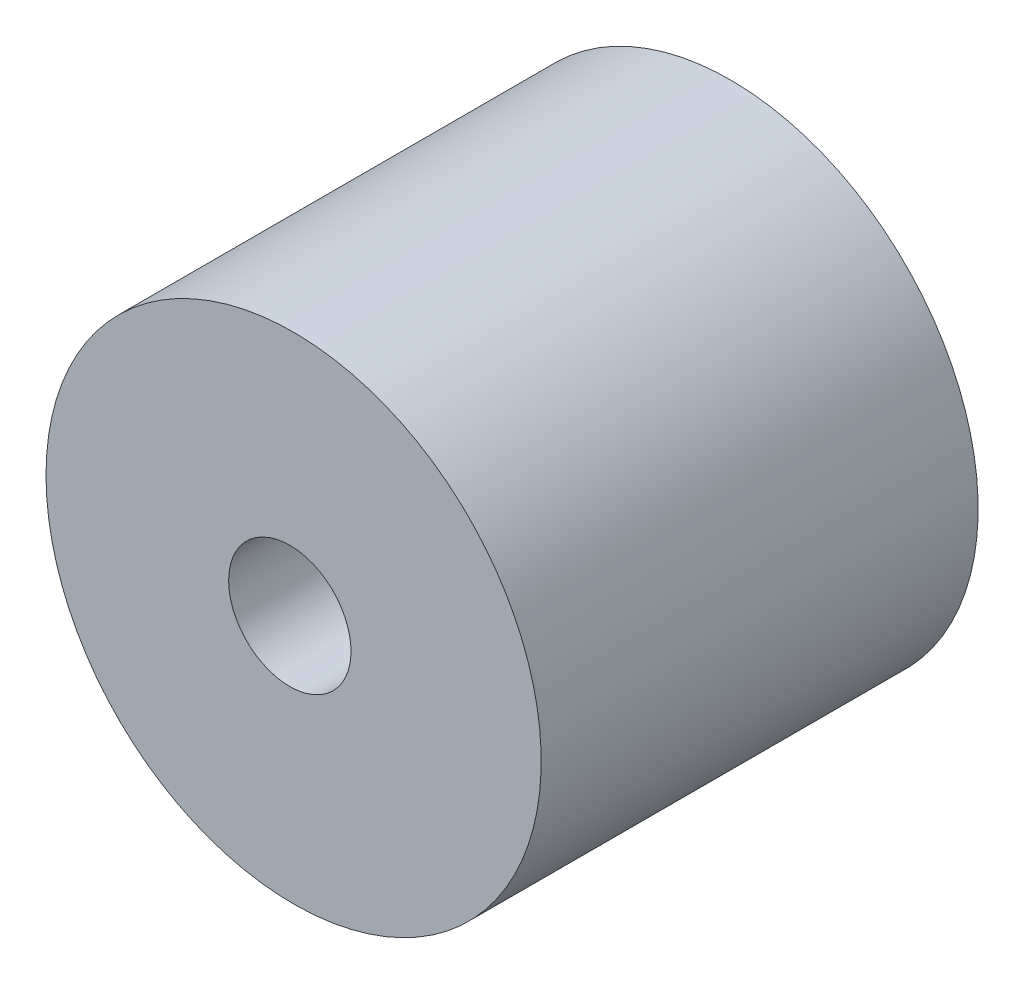
SolidWorks part; units mm, degrees
material "ABS"
ref_plane "Front Plane" through (0, 0, 0) normal (0, 0, 1) x (1, 0, 0)
ref_plane "Top Plane" through (0, 0, 0) normal (0, 1, 0) x (1, 0, 0)
ref_plane "Right Plane" through (0, 0, 0) normal (1, 0, 0) x (0, 0, -1)
sketch "Sketch1" plane through (0, 0, 0) normal (0, 0, 1) x (1, 0, 0)
  circle A0 centre (0, 0) radius 2.667
  circle A1 centre (0.1654, 0) radius 10.795
  dimension "D1" = 5.334
  dimension "D2" = 21.59
extrude "Boss-Extrude1" add sketch "Sketch1" along normal blind 19.05
